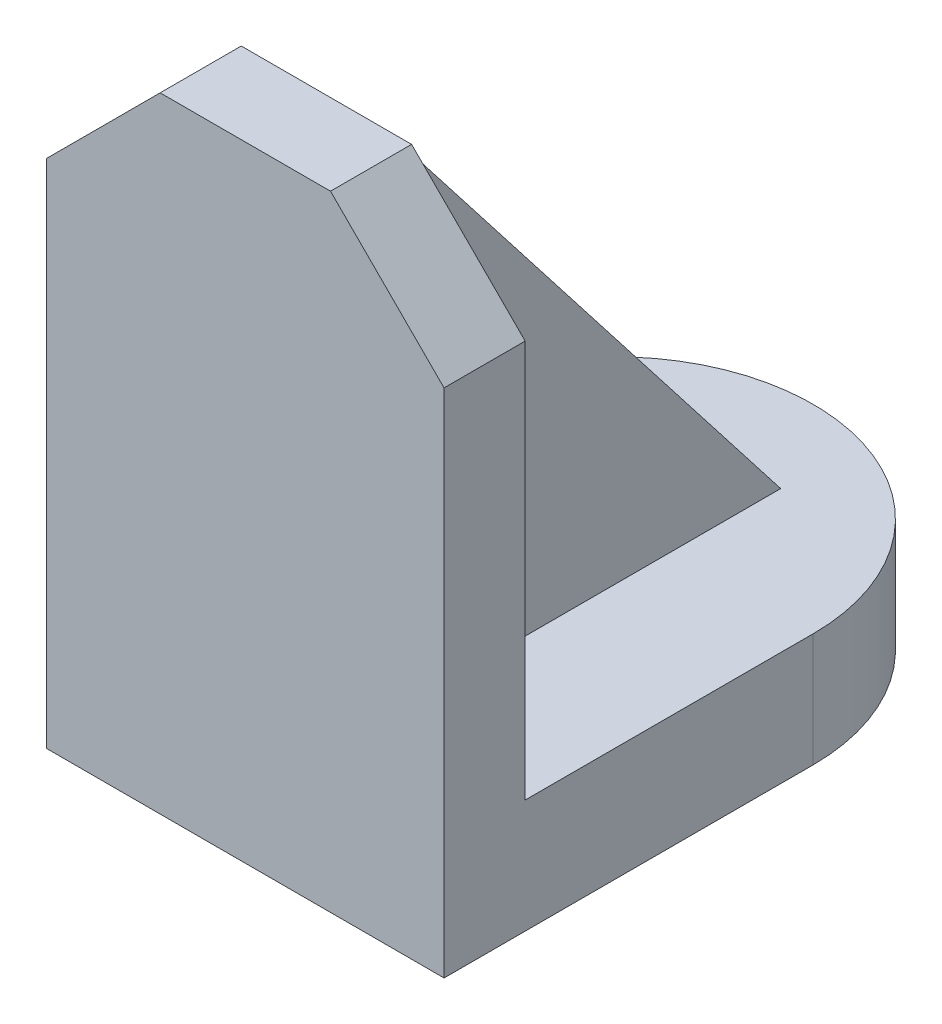
SolidWorks part; units mm, degrees
ref_plane "Front Plane" through (0, 0, 0) normal (0, 0, 1) x (1, 0, 0)
ref_plane "Top Plane" through (0, 0, 0) normal (0, 1, 0) x (1, 0, 0)
ref_plane "Right Plane" through (0, 0, 0) normal (1, 0, 0) x (0, 0, -1)
sketch "Sketch1" plane through (0, 0, 0) normal (0, 1, 0) x (1, 0, 0)
  line L1 (21, -19.5) -> (-21, -19.5)
  line L2 (21, -19.5) -> (21, 19.5)
  line L3 (21, 19.5) -> (-21, 19.5)
  line L4 (-21, -19.5) -> (-21, 19.5)
  line L5 (21, -19.5) -> (-21, 19.5) construction
  line L6 (21, 19.5) -> (-21, -19.5) construction
  arc A0 (-21, 19.5) -> (21, 19.5) centre (0, 19.5) cw
  point P0 (0, 0)
  dimension "D1" = 39
  dimension "D2" = 42
extrude "Boss-Extrude1" add sketch "Sketch1" along normal blind 12 contours L4 L1 L2 L3 | A0 L3
sketch "Sketch2" plane through (0, 12, 0) normal (0, 1, 0) x (1, 0, 0)
  line L0 (21, -19.5) -> (21, 19.5) construction
  line L1 (-21, -19.5) -> (21, -19.5)
  line L2 (-21, -19.5) -> (-21, -10.9295)
  line L3 (-21, -10.9295) -> (21, -10.9295)
  line L4 (21, -19.5) -> (21, -10.9295)
extrude "Boss-Extrude2" add sketch "Sketch2" along normal blind 54
chamfer "Chamfer1" distance 12 2 edges at (21, 66, 15.2147) (-21, 66, 15.2147)
sketch "Sketch5" plane through (0, 0, 0) normal (1, 0, 0) x (0, 0, -1)
  line L0 (-10.9295, 66) -> (-10.9295, 12)
  line L1 (-10.9295, 12) -> (31.0705, 12)
  line L2 (40.5, 12) -> (19.5, 12) construction
  line L3 (31.0705, 12) -> (-10.9295, 66)
  dimension "D1" = 42
extrude "Boss-Extrude3" add sketch "Sketch5" along normal mid plane 12
